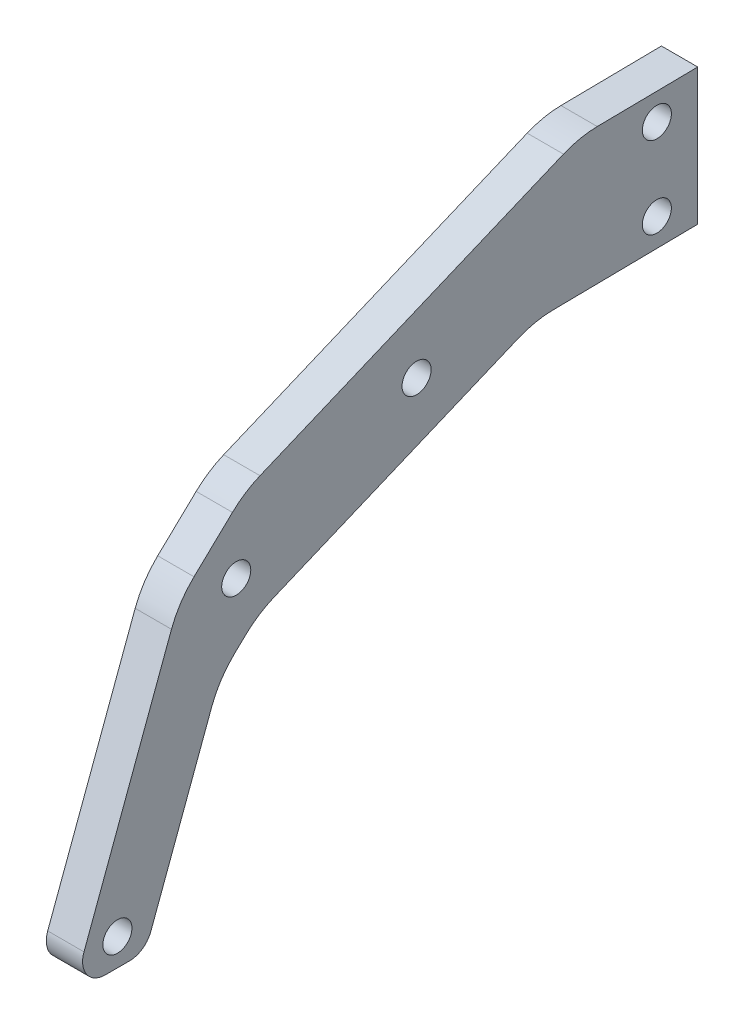
SolidWorks part; units mm, degrees
ref_plane "Front Plane" through (0, 0, 0) normal (0, 0, 1) x (1, 0, 0)
ref_plane "Top Plane" through (0, 0, 0) normal (0, 1, 0) x (1, 0, 0)
ref_plane "Right Plane" through (0, 0, 0) normal (1, 0, 0) x (0, 0, -1)
sketch "Sketch1" plane through (0, 0, 0) normal (1, 0, 0) x (0, 0, -1)
  line L0 (3.5946, 0) -> (6.2613, 0)
  line L1 (8.605, 1.63) -> (16.1383, 21.9252)
  line L2 (16.1383, 21.9252) -> (20.4267, 26.0029)
  line L3 (20.4267, 26.0029) -> (50.9139, 38.7396)
  line L4 (50.9139, 38.7396) -> (68.8447, 38.9779)
  line L6 (11.6904, 31.495) -> (18.9373, 38.3858)
  line L7 (18.9373, 38.3858) -> (55.8459, 53.8051)
  line L10 (68.8447, 38.9779) -> (68.8447, 53.9779)
  line L13 (1.2509, 3.37) -> (11.6904, 31.495)
  line L14 (55.8459, 53.8051) -> (68.8447, 53.9779)
  line L15 (35.5671, 45.3332) -> (40.1929, 34.2606) construction
  line L16 (14.5715, 34.2345) -> (21.4623, 26.9876) construction
  circle A0 centre (64.3447, 50.9779) radius 1.6
  circle A1 centre (4.928, 3) radius 1.6
  circle A2 centre (18.0169, 30.6111) radius 1.6
  arc A3 (6.2613, 0) -> (8.605, 1.63) centre (6.2613, 2.5) ccw
  arc A4 (3.5946, 0) -> (1.2509, 3.37) centre (3.5946, 2.5) cw
  circle A5 centre (37.88, 39.7969) radius 1.6
  circle A6 centre (64.3403, 41.9779) radius 1.6
  point P11 (37.88, 39.7969)
  point P19 (18.0169, 30.6111)
  point P21 (4.928, 0)
  point P22 (18.0169, 30.6111)
  point P27 (8, 0)
  point P30 (0, 0)
  point P34 (68.8447, 46.4779)
  dimension "D2" = 3.2
  dimension "D6" = 2.5
  dimension "D1" = 8
  dimension "D3" = 4.5
  dimension "D4" = 15
  dimension "D5" = 3
  dimension "D7" = 10
  dimension "D8" = 7.5
  dimension "D9" = 12
  dimension "D10" = 40
  dimension "D11" = 10
  dimension "D12" = 30
  dimension "D13" = 13
  dimension "D14" = 9
  dimension "D15" = 4.5
extrude "Boss-Extrude1" add sketch "Sketch1" along normal blind 4 contours A0 | A5 | A2 | A1 | A6 | L13 L6 L7 L14 L10 L4 L3 L2 L1 A3 L0 A4
fillet "Fillet1" radius 10 6 edges at (2, 53.8051, -55.8459) (2, 31.495, -11.6904) (2, 38.3858, -18.9373) (2, 21.9252, -16.1383) (2, 26.0029, -20.4267) (2, 38.7396, -50.9139)
